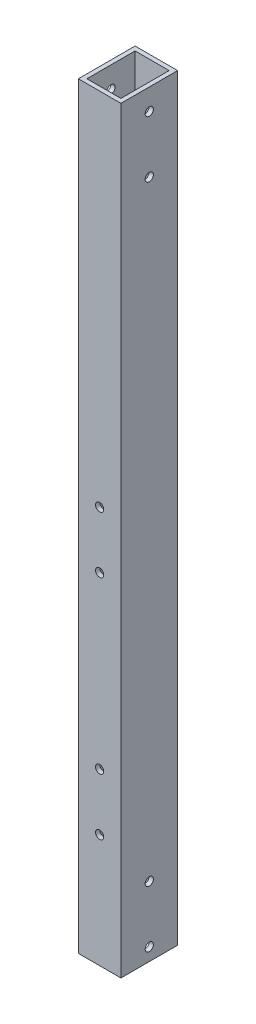
SolidWorks part; units mm, degrees
material "Thornel Mat VMA"
ref_plane "前视基准面" through (0, 0, 0) normal (0, 0, 1) x (1, 0, 0)
ref_plane "上视基准面" through (0, 0, 0) normal (0, 1, 0) x (1, 0, 0)
ref_plane "右视基准面" through (0, 0, 0) normal (1, 0, 0) x (0, 0, -1)
sketch "草图1" plane through (0, 0, 0) normal (0, 1, 0) x (1, 0, 0)
  line L1 (-7.5, -10) -> (7.5, -10)
  line L2 (-7.5, -10) -> (-7.5, 10)
  line L3 (-7.5, 10) -> (7.5, 10)
  line L4 (7.5, -10) -> (7.5, 10)
  line L5 (-7.5, -10) -> (7.5, 10) construction
  line L6 (-7.5, 10) -> (7.5, -10) construction
  point P0 (0, 0)
  dimension "D1" = 20
  dimension "D2" = 15
extrude "拉伸-薄壁1" add sketch "草图1" along normal blind 267 thin thin type one direction reverse wall 1.5
sketch "草图4" plane through (7.5, 0, 0) normal (1, 0, 0) x (0, 0, -1)
  line L0 (0, 0) -> (0, 267) construction
  line L1 (-10, 267) -> (10, 267) construction
  line L2 (-10, 0) -> (10, 0) construction
  circle A0 centre (0, 259.5) radius 1.45
  circle A1 centre (0, 239.5) radius 1.45
  circle A2 centre (0, 24.5) radius 1.45
  circle A3 centre (0, 4.5) radius 1.45
  dimension "D1" = 2.9
  dimension "D5" = 215
  dimension "D2" = 4.5
  dimension "D3" = 20
  dimension "D4" = 20
extrude "切除-拉伸2" cut sketch "草图4" against normal through all
sketch "草图5" plane through (0, 0, 10) normal (0, 0, 1) x (1, 0, 0)
  line L0 (0, 0) -> (0, 267) construction
  line L1 (-7.5, 267) -> (7.5, 267) construction
  line L2 (-7.5, 0) -> (7.5, 0) construction
  circle A0 centre (0, 40) radius 1.45
  circle A1 centre (0, 60) radius 1.45
  circle A2 centre (0, 120) radius 1.45
  circle A3 centre (0, 140) radius 1.45
  dimension "D1" = 2.9
  dimension "D2" = 20
  dimension "D3" = 20
  dimension "D4" = 60
  dimension "D5" = 40
extrude "切除-拉伸3" cut sketch "草图5" against normal through all
